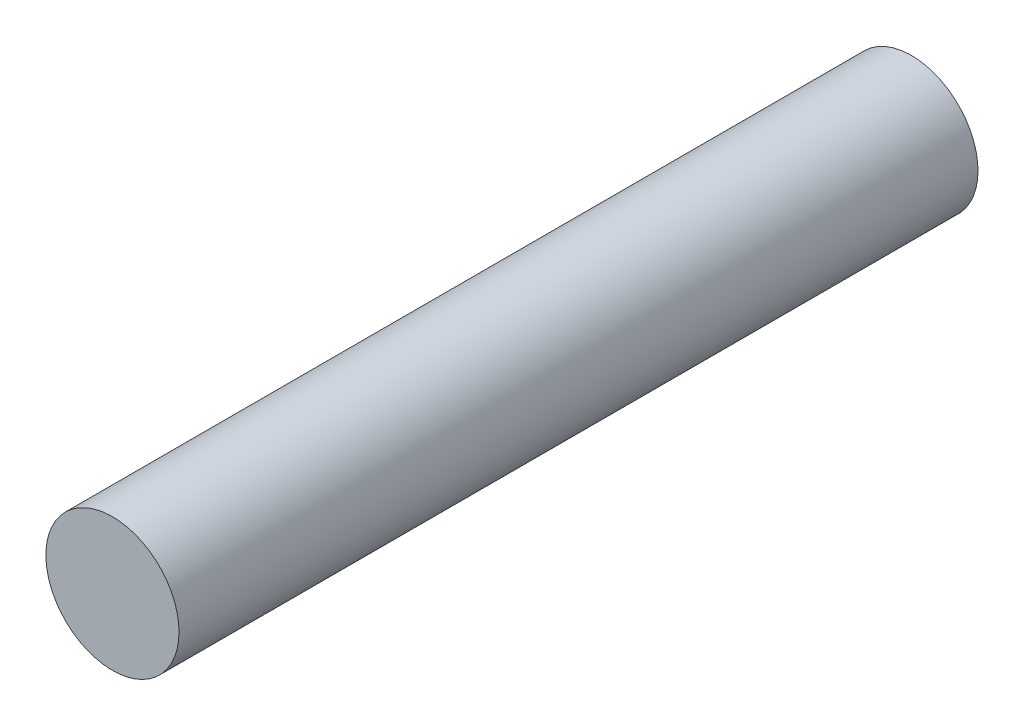
SolidWorks part; units mm, degrees
ref_plane "Front Plane" through (0, 0, 0) normal (0, 0, 1) x (1, 0, 0)
ref_plane "Top Plane" through (0, 0, 0) normal (0, 1, 0) x (1, 0, 0)
ref_plane "Right Plane" through (0, 0, 0) normal (1, 0, 0) x (0, 0, -1)
sketch "Sketch1" plane through (0, 0, 0) normal (0, 0, 1) x (1, 0, 0)
  circle A0 centre (0, 0) radius 2
  dimension "D1" = 4
extrude "Boss-Extrude1" add sketch "Sketch1" along normal blind 24
